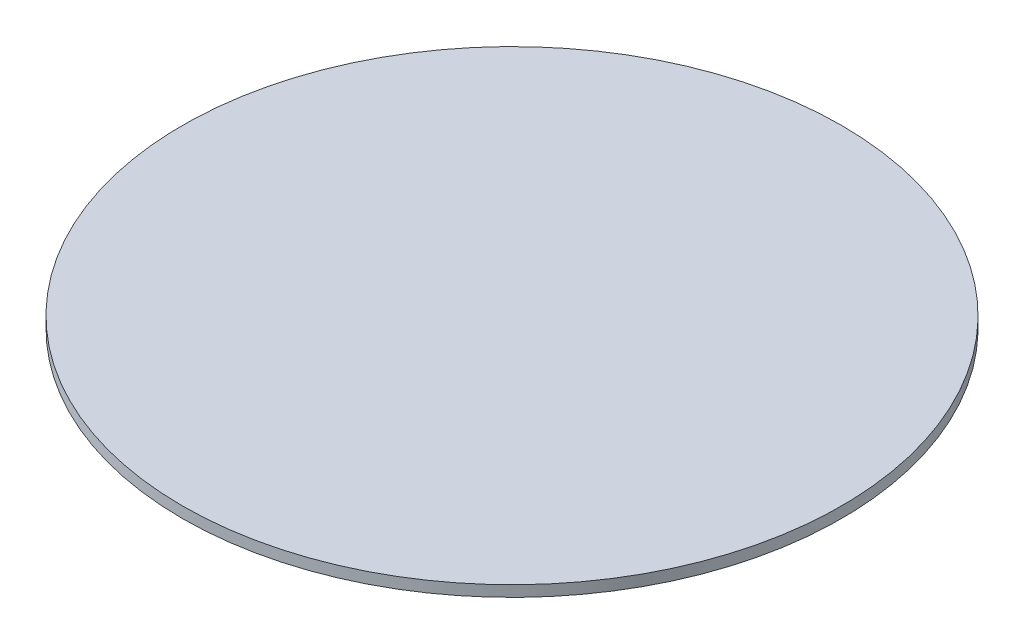
SolidWorks part; units mm, degrees
ref_plane "Front Plane" through (0, 0, 0) normal (0, 0, 1) x (1, 0, 0)
ref_plane "Top Plane" through (0, 0, 0) normal (0, 1, 0) x (1, 0, 0)
ref_plane "Right Plane" through (0, 0, 0) normal (1, 0, 0) x (0, 0, -1)
sketch "Sketch2" plane through (0, 0, 0) normal (0, 1, 0) x (1, 0, 0)
  circle A0 centre (0, 0) radius 152.4
  dimension "D1" = 304.8
extrude "Boss-Extrude1" add sketch "Sketch2" along normal blind 5.08
